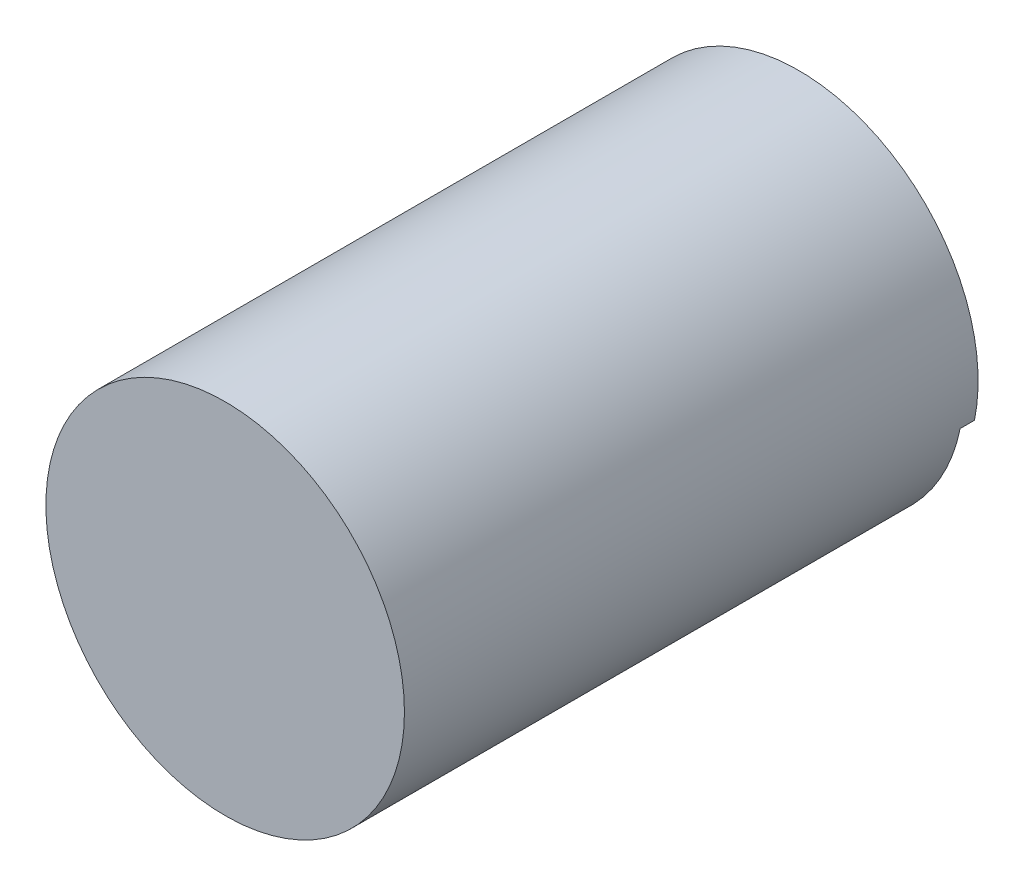
SolidWorks part; units mm, degrees
ref_plane "前视基准面" through (0, 0, 0) normal (0, 0, 1) x (1, 0, 0)
ref_plane "上视基准面" through (0, 0, 0) normal (0, 1, 0) x (1, 0, 0)
ref_plane "右视基准面" through (0, 0, 0) normal (1, 0, 0) x (0, 0, -1)
other "Configuration Table"
sketch "草图1" plane through (0, 0, 0) normal (0, 0, 1) x (1, 0, 0)
  circle A0 centre (0, 0) radius 25
  dimension "D1" = 50
extrude "凸台-拉伸1" add sketch "草图1" along normal blind 80
sketch "草图2" plane through (0, 0, 0) normal (0, 0, -1) x (-1, 0, 0)
  line L0 (0, 0) -> (0, -5) construction
  line L1 (0, -25) -> (0, -5) construction
  line L2 (0, 0) -> (21.6506, -12.5) construction
  line L3 (19.0748, -11.0128) -> (21.6506, -12.5)
  arc A0 (19.0748, -11.0128) -> (0, 15) centre (0, -5) ccw
  circle A1 centre (0, 0) radius 25 construction
  arc A2 (0, 15) -> (-24.4949, -5) centre (0, -10) ccw
  arc A4 (-24.4949, -5) -> (21.6506, -12.5) centre (0, 0) ccw
  point P3 (0, 15)
  point P7 (0, 25)
  point P12 (0, 0)
  point P13 (0, -25)
  point P14 (0, 0)
  point P15 (0, -15)
  point P16 (0, 0)
  point P17 (-24.6671, -4.0664)
  point P18 (-21.8989, -12.0597)
  point P19 (0, 0)
  point P20 (-24.8698, -2.5478)
  point P21 (0, 0)
  dimension "D2" = 60
  dimension "D1" = 10
  dimension "D3" = 15
extrude "切除-拉伸1" cut sketch "草图2" against normal blind 2
